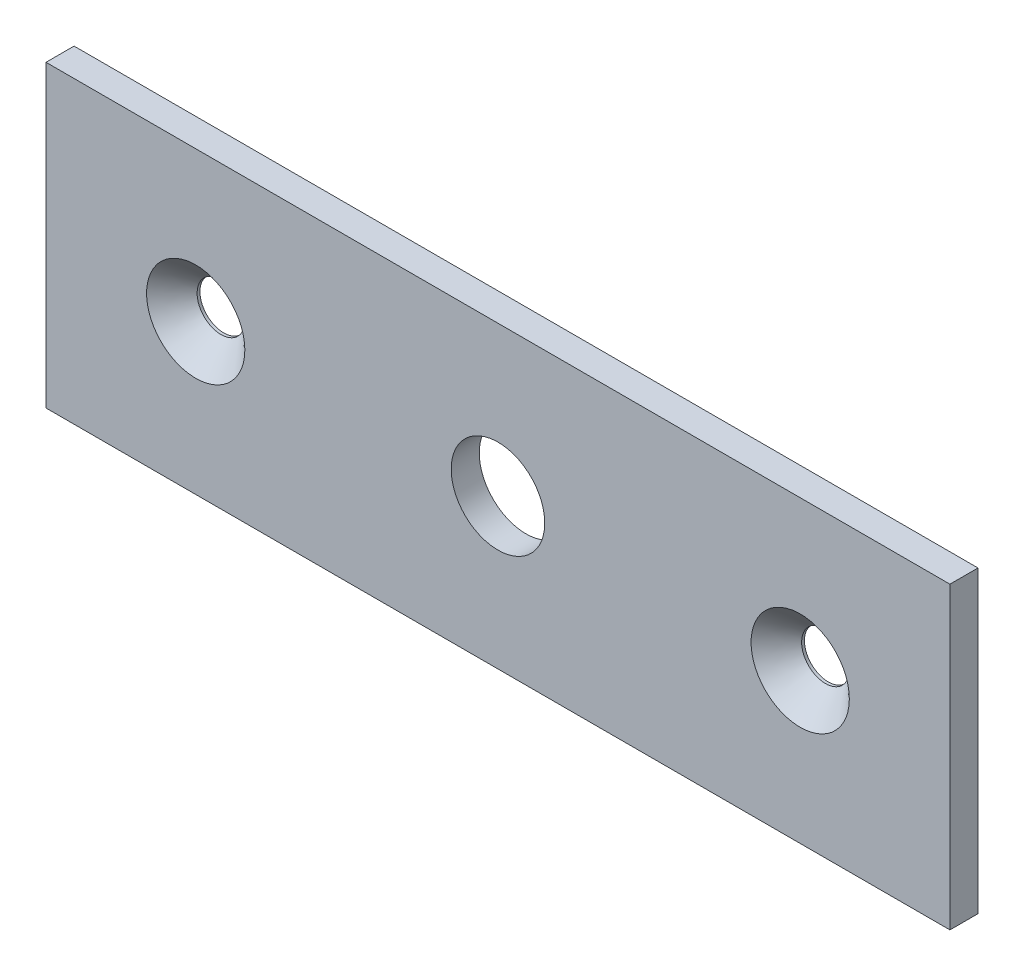
SolidWorks part; units mm, degrees
ref_plane "Plan de face" through (0, 0, 0) normal (0, 0, 1) x (1, 0, 0)
ref_plane "Plan de dessus" through (0, 0, 0) normal (0, 1, 0) x (1, 0, 0)
ref_plane "Plan de droite" through (0, 0, 0) normal (1, 0, 0) x (0, 0, -1)
sketch "Sketch1" plane through (0, 0, 0) normal (0, 0, 1) x (1, 0, 0)
  line L1 (-19.8825, 16.6713) -> (76.7175, 16.6713)
  line L2 (-19.8825, 16.6713) -> (-19.8825, -15.3287)
  line L3 (-19.8825, -15.3287) -> (76.7175, -15.3287)
  line L4 (76.7175, 16.6713) -> (76.7175, -15.3287)
  dimension "D1" = 32
  dimension "D2" = 96.6
extrude "Boss-Extrude1" add sketch "Sketch1" along normal blind 3
sketch "Sketch2" plane through (0, 0, 3) normal (0, 0, 1) x (1, 0, 0)
  line L0 (-19.8825, 16.6713) -> (-19.8825, -15.3287) construction
  line L3 (-19.8825, -15.3287) -> (76.7175, -15.3287) construction
  circle A2 centre (28.4175, 0.6713) radius 5
  point P12 (-19.8825, 0.6713)
  dimension "D7" = 48.3
  dimension "D8" = 16
extrude "Cut-Extrude1" cut sketch "Sketch2" against normal through all
sketch "Esquisse2" plane through (0, 0, 3) normal (0, 0, 1) x (1, 0, 0)
  line L0 (-19.8825, 16.6713) -> (-19.8825, -15.3287) construction
  line L1 (76.7175, -15.3287) -> (76.7175, 16.6713) construction
  line L2 (76.7175, 16.6713) -> (-19.8825, 16.6713) construction
  circle A0 centre (-3.8825, 0.6713) radius 5.25
  circle A1 centre (60.7175, 0.6713) radius 5.25
  dimension "D1" = 10.5
  dimension "D2" = 10.5
  dimension "D3" = 16
  dimension "D4" = 16
  dimension "D5" = 16
  dimension "D6" = 16
hole_wizard "Fraisage pour vis à tête fraisée bombée #51" positions "Esquisse3D1" profile "Esquisse3" countersink size "#5" standard "Ansi Inch" end condition through all
sketch3d "Esquisse3D1"
  point P0 (-3.8825, 0.6713, 3)
  point P3 (60.7175, 0.6713, 3)
sketch "Esquisse3" plane through (-3.8825, 0.6713, 3) normal (1, 0, 0) x (0, -1, 0)
  line L0 (0, 0) -> (0, 3)
  line L1 (0, 3) -> (2.55, 3)
  line L2 (2.55, 3) -> (2.55, 2.7)
  line L3 (2.55, 2.7) -> (5.25, 0)
  line L5 (5.25, 0) -> (0, 0)
  line L6 (-2.55, 2.7) -> (-5.25, 0) construction
  line L11 (0, -6.35) -> (0, 107.95) construction
  dimension "Diamètre du perçage jusqu'au prochain" = 5.1
  dimension "Profondeur du perçage jusqu'au prochain" = 3
  dimension "Diamètre du fraisage entrant" = 10.5
  dimension "Angle du fraisage entrant" = 90
